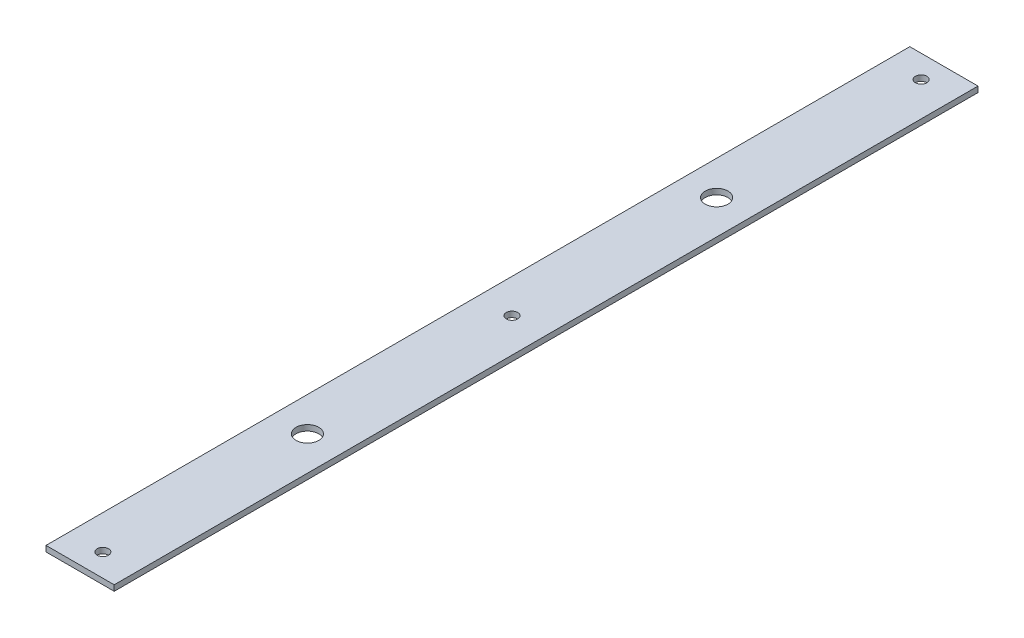
SolidWorks part; units mm, degrees
ref_plane "Front Plane" through (0, 0, 0) normal (0, 0, 1) x (1, 0, 0)
ref_plane "Top Plane" through (0, 0, 0) normal (0, 1, 0) x (1, 0, 0)
ref_plane "Right Plane" through (0, 0, 0) normal (1, 0, 0) x (0, 0, -1)
ref_plane "Plane1"
sketch "Sketch1" plane through (0, 0, 0) normal (0, 1, 0) x (-1, 0, 0)
  line L0 (-19.05, 241.3) -> (19.05, 241.3)
  line L1 (19.05, 241.3) -> (19.05, -241.3)
  line L2 (19.05, -241.3) -> (-19.05, -241.3)
  line L3 (-19.05, -241.3) -> (-19.05, 241.3)
  dimension "D1" = 38.1
  dimension "D2" = 482.6
extrude "Extrusion1" add sketch "Sketch1" along normal blind 3.175
hole_wizard "Hole1" positions "Sketch3" profile "Sketch2" legacy end condition through all
sketch "Sketch3" plane through (0, 3.175, 0) normal (0, 1, 0) x (1, 0, 0)
  point P1 (0, -228.6)
  point P2 (0, 228.6)
  point P3 (0, 0)
sketch "Sketch2" plane through (0, 3.175, 228.6) normal (1, 0, 0) x (0, 0, 1)
  line L0 (0, 0) -> (0, 3.175)
  line L1 (0, 3.175) -> (3.175, 3.175)
  line L2 (3.175, 3.175) -> (3.175, 0)
  line L3 (3.175, 0) -> (0, 0)
  line L4 (0, 110) -> (0, -10) construction
  dimension "Diameter" = 6.35
  dimension "Depth" = 3.175
hole_wizard "Hole2" positions "Sketch5" profile "Sketch4" legacy end condition through all
sketch "Sketch5" plane through (0, 3.175, 0) normal (0, 1, 0) x (1, 0, 0)
  point P1 (0, -101.6)
  point P2 (0, 101.6)
sketch "Sketch4" plane through (0, 3.175, 101.6) normal (1, 0, 0) x (0, 0, 1)
  line L0 (0, 0) -> (0, 3.175)
  line L1 (0, 3.175) -> (6.35, 3.175)
  line L2 (6.35, 3.175) -> (6.35, 0)
  line L3 (6.35, 0) -> (0, 0)
  line L4 (0, 110) -> (0, -10) construction
  dimension "Diameter" = 12.7
  dimension "Depth" = 3.175
ref_plane "Plane2"
sketch "Sketch6" plane through (0, 3.175, 0) normal (0, 1, 0) x (1, 0, 0)
  circle A0 centre (0, -101.6) radius 6.35
  circle A1 centre (0, 101.6) radius 6.35
extrude "Extrusion2" add sketch "Sketch6" against normal blind 3.175 contours A0 | A1
hole_wizard "Hole3" positions "Sketch8" profile "Sketch7" legacy end condition through all
sketch "Sketch8" plane through (0, 3.175, 0) normal (0, 1, 0) x (1, 0, 0)
  point P1 (0, 114.3)
  point P2 (0, -114.3)
sketch "Sketch7" plane through (0, 3.175, -114.3) normal (1, 0, 0) x (0, 0, 1)
  line L0 (0, 0) -> (0, 3.175)
  line L1 (0, 3.175) -> (6.35, 3.175)
  line L2 (6.35, 3.175) -> (6.35, 0)
  line L3 (6.35, 0) -> (0, 0)
  line L4 (0, 110) -> (0, -10) construction
  dimension "Diameter" = 12.7
  dimension "Depth" = 3.175
hole_wizard "Hole4" positions "Sketch10" profile "Sketch9" legacy end condition through all
sketch "Sketch10" plane through (0, 3.175, 0) normal (0, 1, 0) x (1, 0, 0)
  point P1 (0, -88.9)
  point P2 (0, -139.7)
  point P3 (0, 88.9)
  point P4 (0, 139.7)
sketch "Sketch9" plane through (0, 3.175, 88.9) normal (1, 0, 0) x (0, 0, 1)
  line L0 (0, 0) -> (0, 3.175)
  line L1 (0, 3.175) -> (1.9844, 3.175)
  line L2 (1.9844, 3.175) -> (1.9844, 0)
  line L3 (1.9844, 0) -> (0, 0)
  line L4 (0, 110) -> (0, -10) construction
  dimension "Diameter" = 3.9688
  dimension "Depth" = 3.175
ref_plane "Plane3"
sketch "Sketch11" plane through (0, 3.175, 0) normal (0, 1, 0) x (1, 0, 0)
  circle A0 centre (0, 88.9) radius 1.9844
  circle A1 centre (0, -88.9) radius 1.9844
  circle A2 centre (0, -139.7) radius 1.9844
  circle A3 centre (0, 139.7) radius 1.9844
extrude "Extrusion3" add sketch "Sketch11" against normal blind 3.175 contours A0 | A1 | A2 | A3
